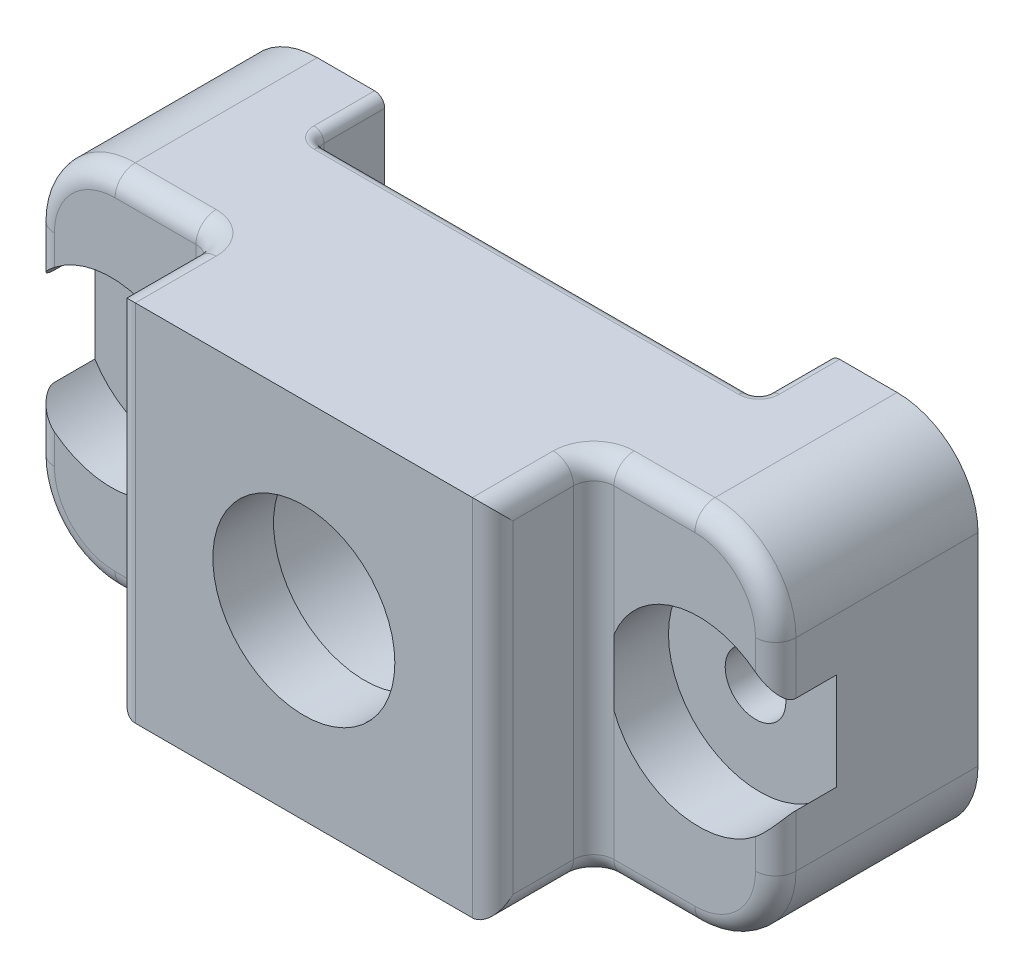
SolidWorks part; units mm, degrees
ref_plane "Front Plane" through (0, 0, 0) normal (0, 0, 1) x (1, 0, 0)
ref_plane "Top Plane" through (0, 0, 0) normal (0, 1, 0) x (1, 0, 0)
ref_plane "Right Plane" through (0, 0, 0) normal (1, 0, 0) x (0, 0, -1)
sketch "Sketch1" plane through (0, 0, 0) normal (0, 0, 1) x (1, 0, 0)
  line L0 (0, 9) -> (0, 13.2219) construction
  line L1 (-14.3348, 9) -> (14.3348, 9)
  line L2 (-18.3348, 5) -> (-18.3348, -5)
  line L3 (-14.3348, -9) -> (14.3348, -9)
  line L4 (18.3348, 5) -> (18.3348, -5)
  line L5 (-18.3348, 9) -> (18.3348, -9) construction
  line L6 (-18.3348, -9) -> (18.3348, 9) construction
  circle A0 centre (0, 0) radius 5.5
  circle A2 centre (-14.3348, 0) radius 1.5
  arc A3 (14.3348, 9) -> (18.3348, 5) centre (14.3348, 5) cw
  arc A4 (14.3348, -9) -> (18.3348, -5) centre (14.3348, -5) ccw
  arc A5 (-18.3348, -5) -> (-14.3348, -9) centre (-14.3348, -5) ccw
  arc A6 (-14.3348, 9) -> (-18.3348, 5) centre (-14.3348, 5) ccw
  circle A7 centre (14.3348, 0) radius 1.5
  dimension "D1" = 11
  dimension "D2" = 9
  dimension "D3" = 3
  dimension "D4" = 4
  dimension "D5" = 4
extrude "Boss-Extrude1" add sketch "Sketch1" along normal blind 15
sketch "Sketch3" plane through (0, 0, 15) normal (0, 0, 1) x (1, 0, 0)
  line L1 (-9.3348, 10.683) -> (-19.3342, 10.683)
  line L2 (-9.3348, 10.683) -> (-9.3348, -11.5423)
  line L3 (-9.3348, -11.5423) -> (-19.3342, -11.5423)
  line L4 (-19.3342, 10.683) -> (-19.3342, -11.5423)
  circle A1 centre (-14.3348, 0) radius 1.5 construction
  dimension "D1" = 5
extrude "Cut-Extrude1" cut sketch "Sketch3" against normal blind 5
fillet "Fillet1" radius 1 9 edges at (-11.8348, 9, 10) (-9.3348, 0, 10) (-11.8348, -9, 10) (-17.1632, -7.8284, 10) (-18.3348, 0, 10) (-17.1632, 7.8284, 10) (-9.3348, 9, 12.5) (-9.3348, -9, 12.5) (-9.3348, 0, 15)
mirror "Mirror1" about plane through (0, 0, 0) normal (1, 0, 0) of "Cut-Extrude1", "Fillet1"
sketch "Sketch4" plane through (0, 0, 15) normal (0, 0, 1) x (1, 0, 0)
  circle A0 centre (0, 0) radius 7.5
  dimension "D1" = 15
extrude "Boss-Extrude2" add sketch "Sketch4" against normal blind 3
sketch "Sketch5" plane through (0, 9, 0) normal (0, 1, 0) x (1, 0, 0)
  line L1 (-11, 3.5) -> (11, 3.5)
  line L2 (-11, 3.5) -> (-11, -3.5)
  line L3 (-11, -3.5) -> (11, -3.5)
  line L4 (11, 3.5) -> (11, -3.5)
  line L5 (-11, 3.5) -> (11, -3.5) construction
  line L6 (-11, -3.5) -> (11, 3.5) construction
  line L7 (14.3348, 0) -> (-14.3348, 0) construction
  point P0 (0, 0)
  dimension "D1" = 22
  dimension "D2" = 3.5
extrude "Cut-Extrude2" cut sketch "Sketch5" against normal through all
sketch "Sketch6" plane through (0, 0, 15) normal (0, 0, 1) x (1, 0, 0)
  circle A0 centre (0, 0) radius 4.5
  dimension "D1" = 9
extrude "Cut-Extrude3" cut sketch "Sketch6" against normal through all
sketch "Sketch7" plane through (0, 0, 10) normal (0, 0, 1) x (1, 0, 0)
  circle A0 centre (-14.5304, 0) radius 4.5
  circle A1 centre (14.5304, 0) radius 4.5
  point P6 (0, 0)
  point P7 (-14.921, 0)
  point P8 (-14.5304, 0)
  point P9 (0, 0)
  point P10 (0, 0)
  point P11 (14.5304, 0)
  dimension "D1" = 9
  dimension "D2" = 9
extrude "Cut-Extrude8" cut sketch "Sketch7" against normal blind 3
fillet "Fillet3" radius 0.5 8 edges at (-11, 0, 3.5) (0, -9, 3.5) (11, 0, 3.5) (0, 9, 3.5) (-11, -9, 1.75) (11, -9, 1.75) (11, 9, 1.75) (-11, 9, 1.75)
fillet "Fillet2" radius 0.5 1 edges at (5.5, 0, 12)
